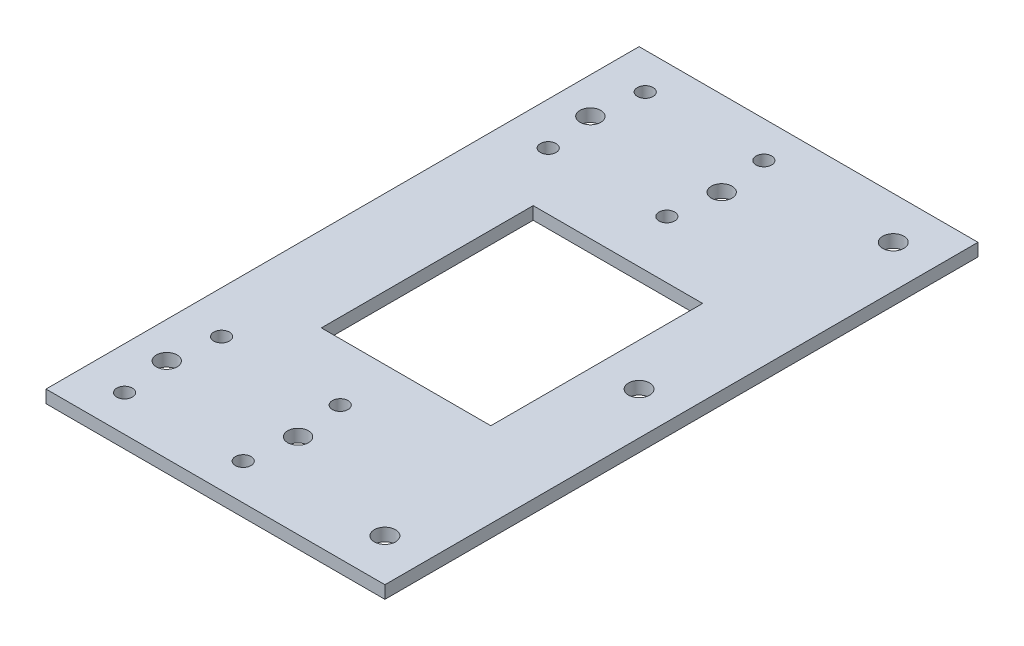
SolidWorks part; units mm, degrees
ref_plane "前视基准面" through (0, 0, 0) normal (0, 0, 1) x (1, 0, 0)
ref_plane "上视基准面" through (0, 0, 0) normal (0, 1, 0) x (1, 0, 0)
ref_plane "右视基准面" through (0, 0, 0) normal (1, 0, 0) x (0, 0, -1)
other "Configuration Table"
sketch "草图1" plane through (0, 0, 0) normal (0, 1, 0) x (1, 0, 0)
  line L0 (-40, 0) -> (49960, 0) construction
  line L1 (-40, -70) -> (40, -70)
  line L2 (-40, -70) -> (-40, 70)
  line L3 (-40, 70) -> (40, 70)
  line L4 (40, -70) -> (40, 70)
  line L5 (-40, -70) -> (40, 70) construction
  line L6 (-40, 70) -> (40, -70) construction
  line L7 (-40, 70) -> (8, 70)
  line L8 (-40, 70) -> (-40, 30)
  line L9 (-40, 30) -> (8, 30)
  line L10 (8, 70) -> (8, 30)
  line L11 (-40, -70) -> (8, -70)
  line L12 (-40, -70) -> (-40, -30)
  line L13 (-40, -30) -> (8, -30)
  line L14 (8, -70) -> (8, -30)
  line L15 (-40, 70) -> (-30, 70)
  line L16 (-40, 70) -> (-40, 61.45)
  line L17 (-40, 61.45) -> (-30, 61.45)
  line L18 (-30, 70) -> (-30, 61.45)
  line L19 (-16, 30) -> (-16, 50030) construction
  line L20 (8, 50) -> (-0.5, 50) construction
  line L22 (40, 70) -> (30, 70)
  line L23 (40, 70) -> (40, 60)
  line L24 (40, 60) -> (30, 60)
  line L25 (30, 70) -> (30, 60)
  circle A0 centre (-30, 61.45) radius 1.85
  circle A1 centre (-2, 61.45) radius 1.85
  circle A2 centre (-2, 38.55) radius 1.85
  circle A3 centre (-30, 38.55) radius 1.85
  circle A4 centre (-0.5, 50) radius 2.45
  circle A5 centre (-31.5, 50) radius 2.45
  circle A6 centre (-2, -38.55) radius 1.85
  circle A7 centre (-0.5, -50) radius 2.45
  circle A8 centre (-2, -61.45) radius 1.85
  circle A9 centre (-30, -38.55) radius 1.85
  circle A10 centre (-31.5, -50) radius 2.45
  circle A11 centre (-30, -61.45) radius 1.85
  circle A12 centre (30, 60) radius 2.5
  circle A13 centre (30, 0) radius 2.5
  circle A14 centre (30, -60) radius 2.5
  point P0 (0, 0)
  point P18 (8, 50)
  point P21 (-16, 30)
  point P33 (-40, 0)
  dimension "D9" = 3.7
  dimension "D11" = 4.9
  dimension "D14" = 5
  dimension "D1" = 80
  dimension "D2" = 140
  dimension "D3" = 40
  dimension "D4" = 48
  dimension "D5" = 48
  dimension "D6" = 40
  dimension "D7" = 10
  dimension "D8" = 8.55
  dimension "D10" = 8.5
  dimension "D12" = 10
  dimension "D13" = 10
  dimension "D15" = 3
extrude "凸台-拉伸1" add sketch "草图1" along normal blind 3 contours A12 L25 L3 L10 L9 L2 L13 L14 L1 L4 L24 A14 A13 | A12 L24 L4 L3 L25 | A0 L17 L2 L9 L10 L7 L18 A3 A2 A1 A4 A5 | A0 L18 L3 L8 L17 | L1 L14 L13 L2 A7 A6 A8 A9 A10 A11
sketch "草图2" plane through (0, 3, 0) normal (0, 1, 0) x (1, 0, 0)
  line L1 (20, -25) -> (-20, -25)
  line L2 (20, -25) -> (20, 25)
  line L3 (20, 25) -> (-20, 25)
  line L4 (-20, -25) -> (-20, 25)
  line L5 (20, -25) -> (-20, 25) construction
  line L6 (20, 25) -> (-20, -25) construction
  point P0 (0, 0)
  dimension "D1" = 40
  dimension "D2" = 50
extrude "切除-拉伸1" cut sketch "草图2" against normal up to next
